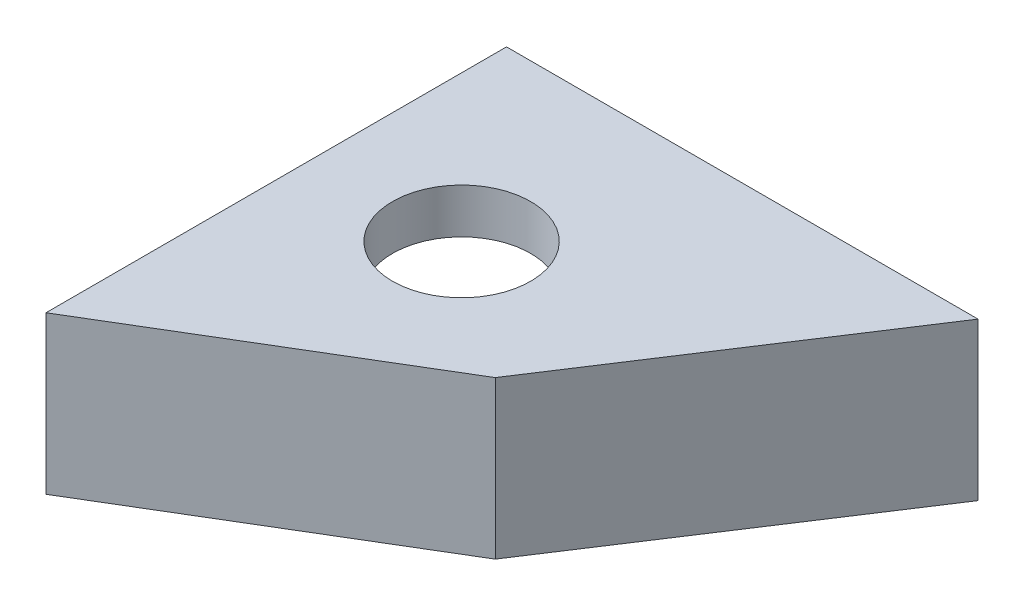
SolidWorks part; units mm, degrees
ref_plane "Front Plane" through (0, 0, 0) normal (0, 0, 1) x (1, 0, 0)
ref_plane "Top Plane" through (0, 0, 0) normal (0, 1, 0) x (1, 0, 0)
ref_plane "Right Plane" through (0, 0, 0) normal (1, 0, 0) x (0, 0, -1)
sketch "Sketch1" plane through (0, 0, 0) normal (0, 1, 0) x (1, 0, 0)
  line L1 (69.8823, -141.1569) -> (82.3823, -133.6569)
  line L8 (69.8823, -141.1569) -> (69.8823, -120.6569)
  line L11 (69.8823, -120.6569) -> (90.8715, -120.6569)
  line L13 (90.8715, -120.6569) -> (82.3823, -133.6569)
  circle A0 centre (76.3823, -129.1569) radius 3.075
  point P3 (0, 0)
  point P9 (0, 0)
  point P12 (81.4678, -133.32)
  dimension "D2" = 6.15
  dimension "D3" = 20.5
  dimension "D1" = 8.5
  dimension "D4" = 4.5
  dimension "D5" = 6
  dimension "D6" = 20.9892
  dimension "D7" = 6.5
extrude "Boss-Extrude1" add sketch "Sketch1" along normal blind 2
sketch "Sketch2" plane through (0, 0, 0) normal (0, -1, 0) x (-1, 0, 0)
  line L0 (-69.8823, -141.1569) -> (-82.3823, -133.6569)
  line L1 (-82.3823, -133.6569) -> (-90.8715, -120.6569)
  line L3 (-71.8823, -138.2076) -> (-69.8823, -139.4569)
  line L4 (-69.8823, -120.6569) -> (-69.8823, -141.1569) construction
  line L5 (-69.8823, -139.4569) -> (-69.8823, -141.1569)
  line L6 (-71.8823, -138.2076) -> (-74.8426, -136.4315)
  line L8 (-90.8715, -120.6569) -> (-80.3, -131.836)
  line L9 (-80.3, -131.836) -> (-74.8426, -136.4315)
  dimension "D1" = 1.7
  dimension "D2" = 2
  dimension "D4" = 1.5
extrude "Boss-Extrude2" add sketch "Sketch2" along normal blind 5
